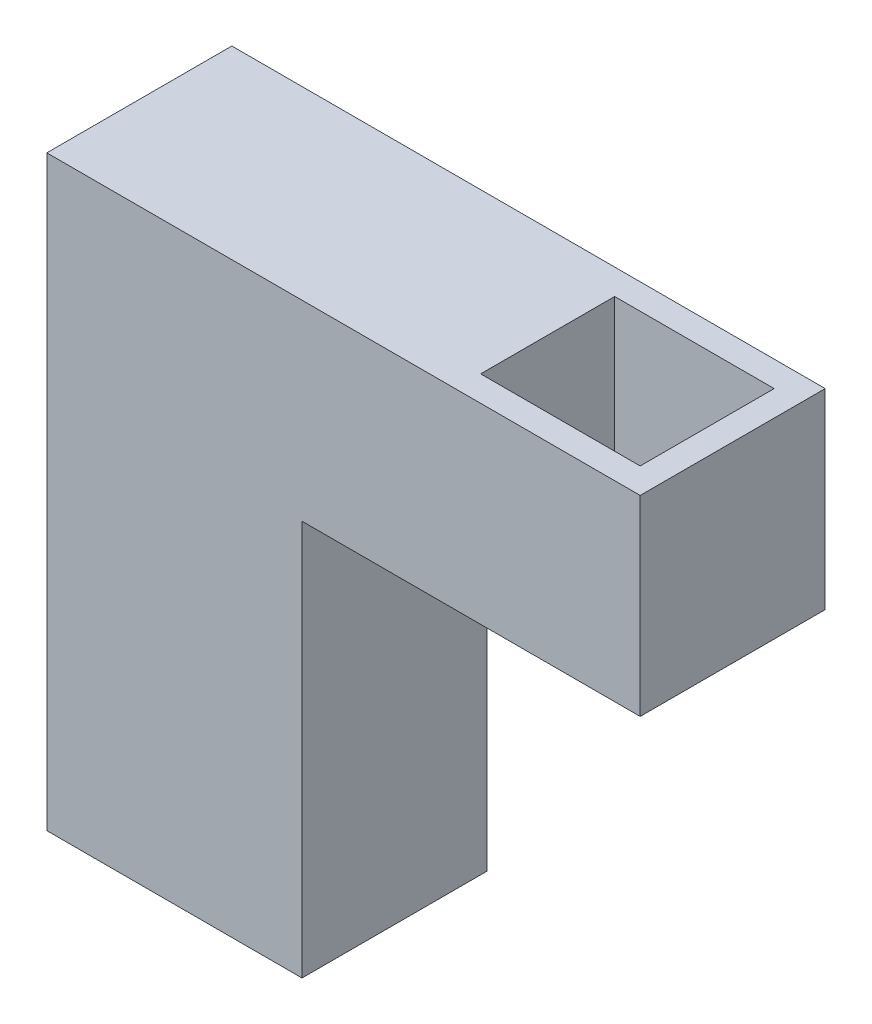
SolidWorks part; units mm, degrees
ref_plane "Front Plane" through (0, 0, 0) normal (0, 0, 1) x (1, 0, 0)
ref_plane "Top Plane" through (0, 0, 0) normal (0, 1, 0) x (1, 0, 0)
ref_plane "Right Plane" through (0, 0, 0) normal (1, 0, 0) x (0, 0, -1)
sketch "Sketch1" plane through (0, 0, 0) normal (0, 1, 0) x (1, 0, 0)
  line L0 (-2, 2) -> (-2, -12.5)
  line L1 (0, 0) -> (12.5, 0)
  line L2 (0, 0) -> (0, -10.5)
  line L3 (0, -10.5) -> (12.5, -10.5)
  line L4 (12.5, 0) -> (12.5, -10.5)
  line L5 (-2, -12.5) -> (14.5, -12.5)
  line L6 (14.5, 2) -> (14.5, -12.5)
  line L7 (-2, 2) -> (14.5, 2)
  dimension "D1" = 12.5
  dimension "D2" = 10.5
  dimension "D3" = 2
extrude "Boss-Extrude1" add sketch "Sketch1" along normal blind 15
sketch "Sketch2" plane through (-2, 0, 0) normal (-1, 0, 0) x (0, 0, 1)
  line L1 (12.5, 0) -> (-2, 0)
  line L2 (12.5, 0) -> (12.5, 15)
  line L3 (12.5, 15) -> (-2, 15)
  line L4 (-2, 0) -> (-2, 15)
extrude "Boss-Extrude2" add sketch "Sketch2" along normal blind 30
sketch "Sketch3" plane through (0, 0, 0) normal (0, -1, 0) x (-1, 0, 0)
  line L0 (32, -12.5) -> (-14.5, -12.5) construction
  line L1 (32, 2) -> (12, 2)
  line L2 (32, 2) -> (32, -12.5)
  line L3 (32, -12.5) -> (12, -12.5)
  line L4 (12, 2) -> (12, -12.5)
  dimension "D1" = 20
extrude "Boss-Extrude3" add sketch "Sketch3" along normal blind 31
